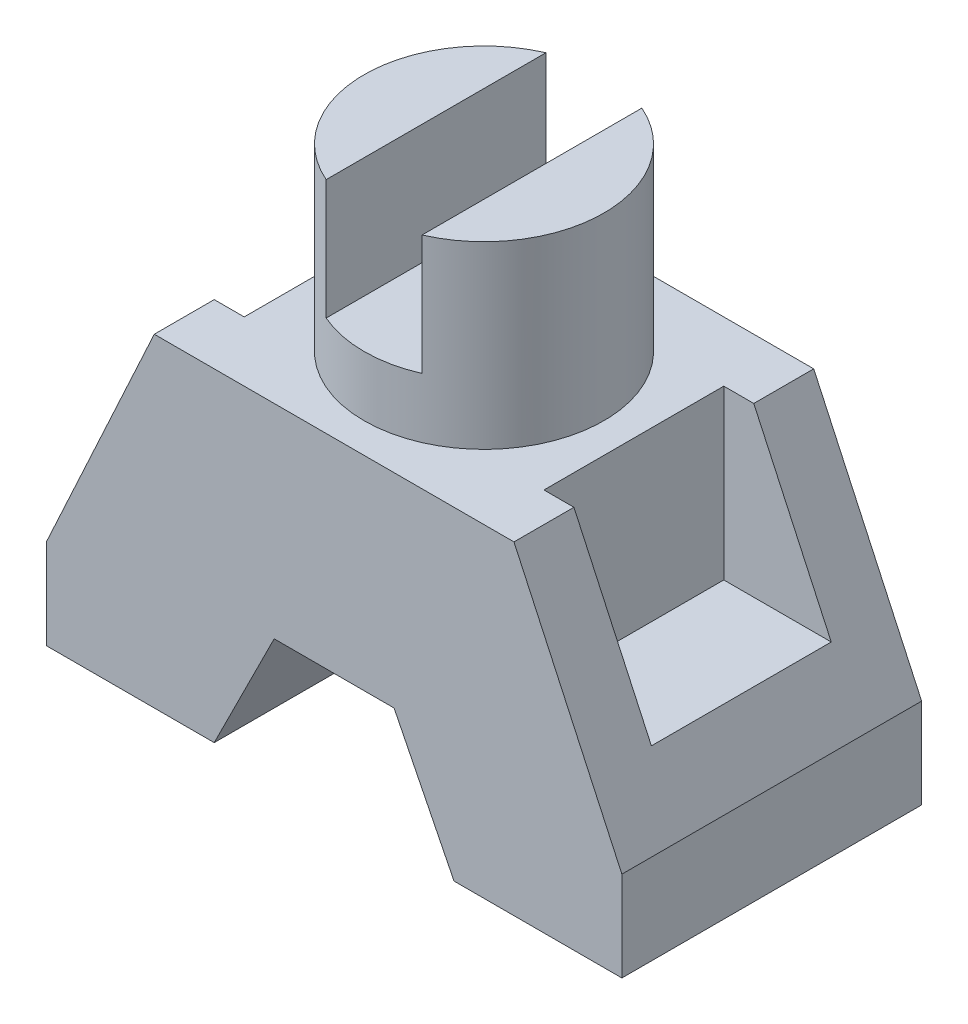
SolidWorks part; units mm, degrees
ref_plane "Front Plane" through (0, 0, 0) normal (0, 0, 1) x (1, 0, 0)
ref_plane "Top Plane" through (0, 0, 0) normal (0, 1, 0) x (1, 0, 0)
ref_plane "Right Plane" through (0, 0, 0) normal (1, 0, 0) x (0, 0, -1)
sketch "Sketch1" plane through (0, 0, 0) normal (0, 0, 1) x (1, 0, 0)
  line L0 (-63.4075, -32.477) -> (-35.4075, -32.477)
  line L1 (32.5925, -32.477) -> (32.5925, -17.477)
  line L2 (-63.4075, -32.477) -> (-63.4075, -17.477)
  line L3 (-63.4075, -32.477) -> (-35.4075, -32.477)
  line L4 (4.5925, -32.477) -> (32.5925, -32.477)
  line L5 (32.5925, -32.477) -> (32.5925, -17.477)
  line L6 (-25.4075, -12.477) -> (-5.4075, -12.477)
  line L9 (4.5925, -32.477) -> (-5.4075, -12.477)
  line L10 (-25.4075, -12.477) -> (-35.4075, -32.477)
  line L12 (14.5925, 21.523) -> (32.5925, -17.477)
  line L13 (14.5925, 21.523) -> (-45.4075, 21.523)
  line L14 (-45.4075, 21.523) -> (-63.4075, -17.477)
extrude "Boss-Extrude1" add sketch "Sketch1" along normal blind 50 contours L13 L14 L2 L0 L10 L6 L9 L4 L1 L12
sketch "Sketch2" plane through (0, 21.523, 0) normal (0, 1, 0) x (1, 0, 0)
  line L0 (14.5925, 0) -> (-45.4075, 0) construction
  line L1 (14.5925, -50) -> (14.5925, 0) construction
  circle A0 centre (-15.4075, -25) radius 20
  dimension "D1" = 25
  dimension "D2" = 30
extrude "Boss-Extrude2" add sketch "Sketch2" along normal blind 30
sketch "Sketch3" plane through (0, 51.523, 0) normal (0, 1, 0) x (1, 0, 0)
  line L1 (-7.4075, -25) -> (-7.4075, -6.6697)
  line L2 (-7.4075, -25) -> (-7.4075, -43.3303)
  line L4 (-23.4075, -43.3303) -> (-23.4075, -6.6697)
  circle A0 centre (-15.4075, -25) radius 20 construction
  circle A1 centre (-15.4075, -25) radius 20 construction
  arc A2 (-23.4075, -43.3303) -> (-7.4075, -43.3303) centre (-15.4075, -25) ccw
  arc A3 (-7.4075, -6.6697) -> (-23.4075, -6.6697) centre (-15.4075, -25) ccw
extrude "Cut-Extrude1" cut sketch "Sketch3" against normal blind 20
ref_plane "Plane1" through (-15.4075, 0, 0) normal (1, 0, 0) x (0, 0, -1)
sketch "Sketch4" plane through (-63.4075, 0, 0) normal (-1, 0, 0) x (0, 0, 1)
  line L1 (10, 21.523) -> (40, 21.523)
  line L4 (10, 21.523) -> (10, -6.477)
  line L5 (10, -6.477) -> (40, -6.477)
  line L6 (40, -6.477) -> (40, 21.523)
extrude "Cut-Extrude2" cut sketch "Sketch4" against normal blind 23
mirror "Mirror1" about plane through (-15.4075, 0, 0) normal (1, 0, 0) of "Cut-Extrude2"
